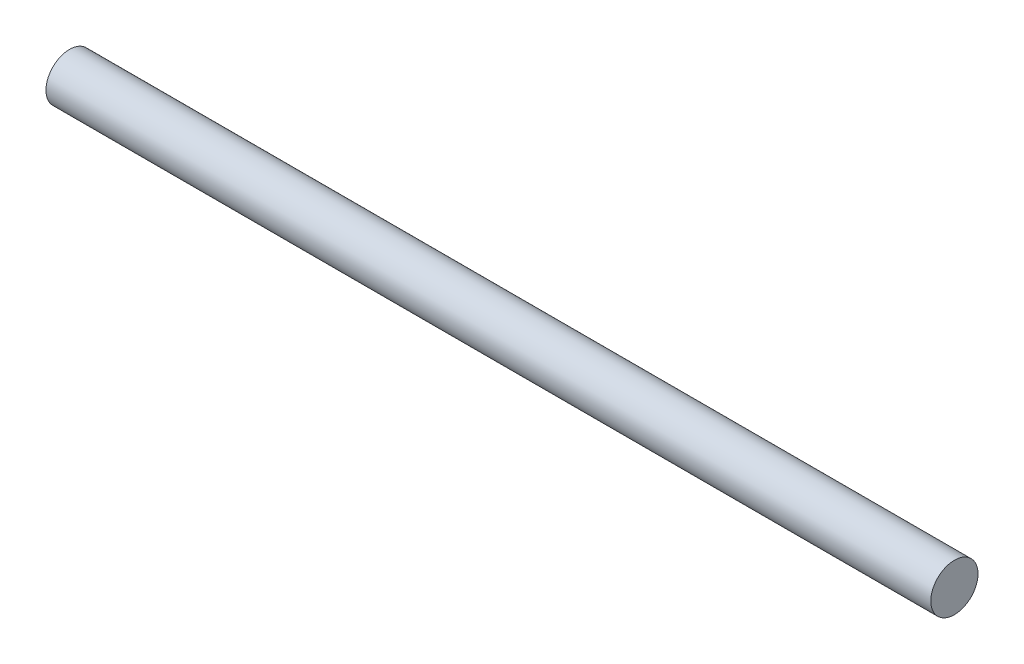
SolidWorks part; units mm, degrees
ref_plane "前视基准面" through (0, 0, 0) normal (0, 0, 1) x (1, 0, 0)
ref_plane "上视基准面" through (0, 0, 0) normal (0, 1, 0) x (1, 0, 0)
ref_plane "右视基准面" through (0, 0, 0) normal (1, 0, 0) x (0, 0, -1)
sketch "草图1" plane through (0, 0, 0) normal (1, 0, 0) x (0, 0, -1)
  circle A0 centre (0, 0) radius 4
extrude "凸台-拉伸1" add sketch "草图1" along normal blind 150
